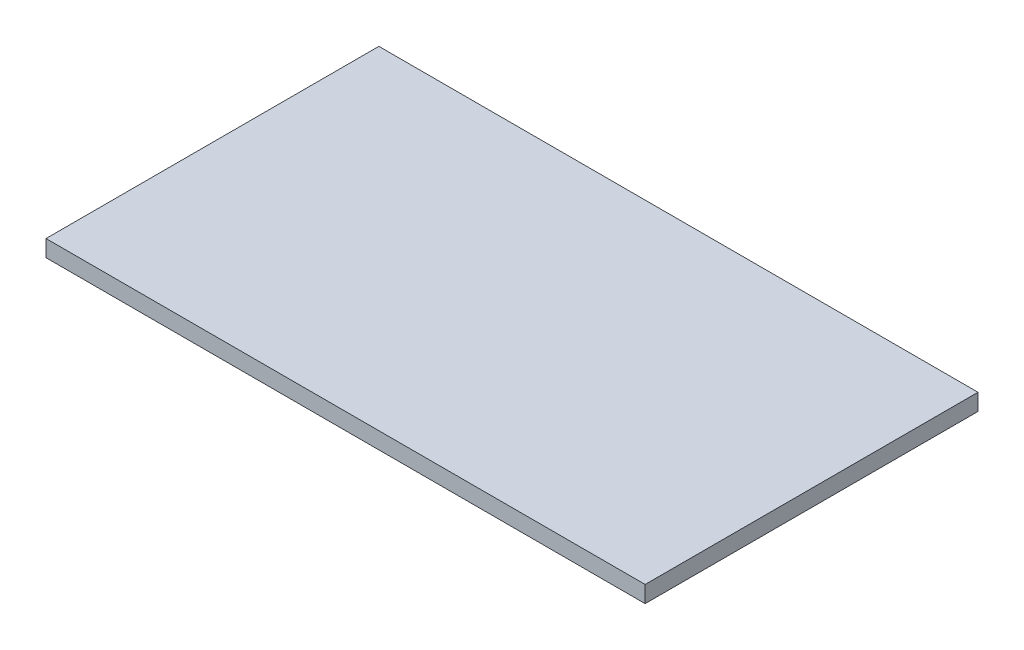
SolidWorks part; units mm, degrees
ref_plane "정면" through (0, 0, 0) normal (0, 0, 1) x (1, 0, 0)
ref_plane "윗면" through (0, 0, 0) normal (0, 1, 0) x (1, 0, 0)
ref_plane "우측면" through (0, 0, 0) normal (1, 0, 0) x (0, 0, -1)
sketch "스케치1" plane through (0, 0, 0) normal (0, 1, 0) x (1, 0, 0)
  line L1 (0, 0) -> (180, 0)
  line L2 (0, 0) -> (0, 100)
  line L3 (0, 100) -> (180, 100)
  line L4 (180, 0) -> (180, 100)
  dimension "D1" = 180
  dimension "D2" = 100
extrude "보스-돌출1" add sketch "스케치1" along normal blind 5
